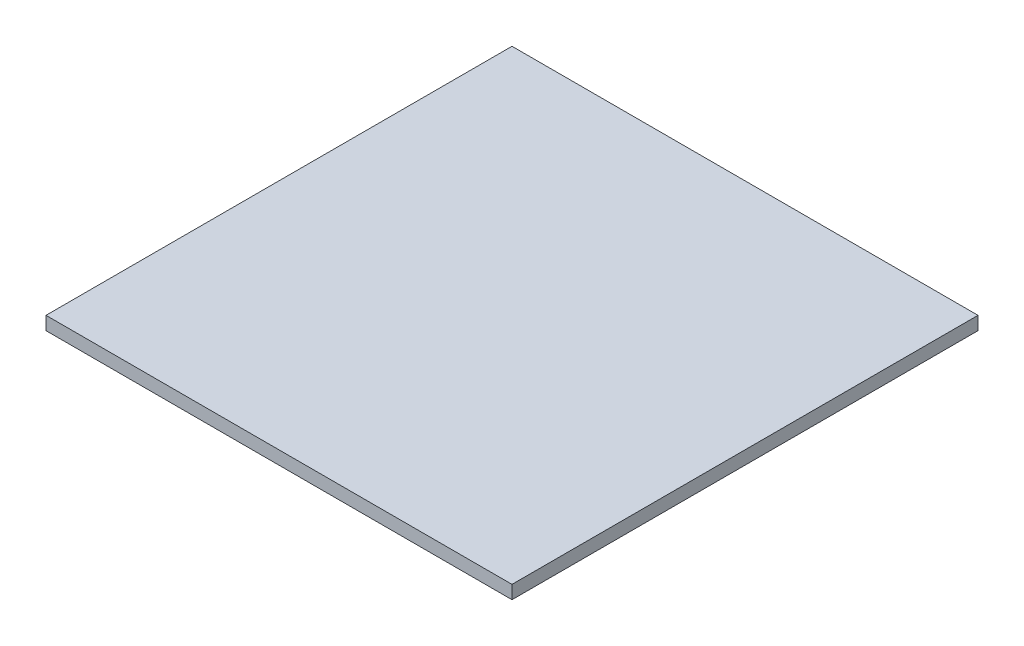
SolidWorks part; units mm, degrees
material "6061-T6 (SS)"
ref_plane "Alzado" through (0, 0, 0) normal (0, 0, 1) x (1, 0, 0)
ref_plane "Planta" through (0, 0, 0) normal (0, 1, 0) x (1, 0, 0)
ref_plane "Vista lateral" through (0, 0, 0) normal (1, 0, 0) x (0, 0, -1)
sketch "Sketch1" plane through (0, 0, 0) normal (0, 1, 0) x (1, 0, 0)
  line L1 (-52.5, 52.5) -> (52.5, 52.5)
  line L2 (-52.5, 52.5) -> (-52.5, -52.5)
  line L3 (-52.5, -52.5) -> (52.5, -52.5)
  line L4 (52.5, 52.5) -> (52.5, -52.5)
  line L5 (-52.5, 52.5) -> (52.5, -52.5) construction
  line L6 (-52.5, -52.5) -> (52.5, 52.5) construction
  point P0 (0, 0)
  dimension "D1" = 105
  dimension "D2" = 105
extrude "Boss-Extrude1" add sketch "Sketch1" along normal blind 3
